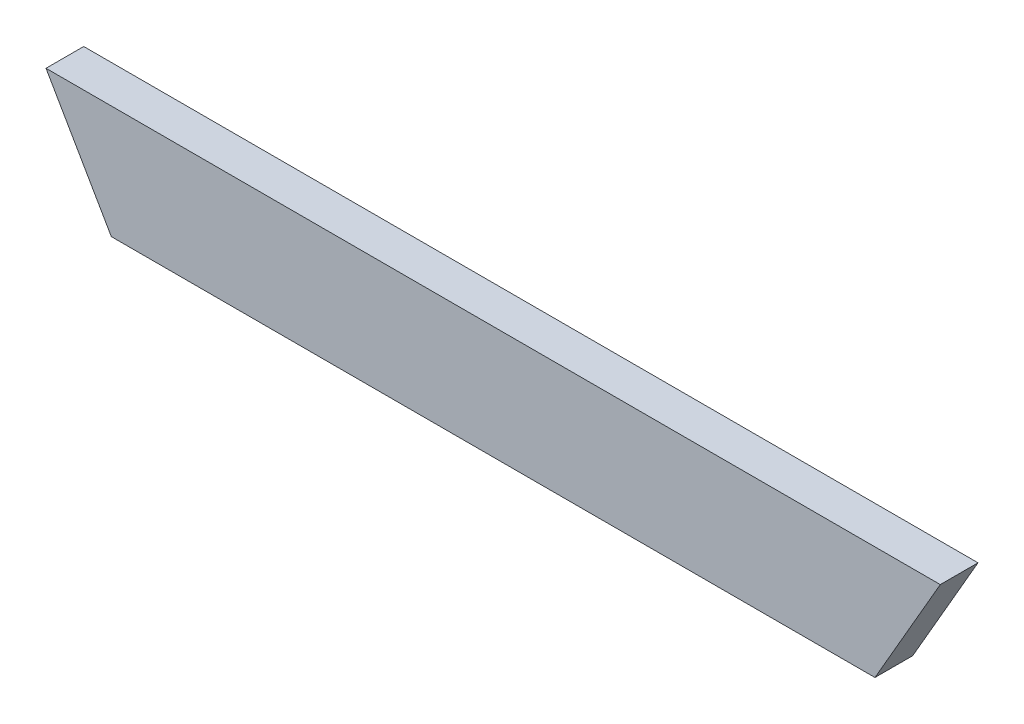
SolidWorks part; units mm, degrees
ref_plane "Plan de face" through (0, 0, 0) normal (0, 0, 1) x (1, 0, 0)
ref_plane "Plan de dessus" through (0, 0, 0) normal (0, 1, 0) x (1, 0, 0)
ref_plane "Plan de droite" through (0, 0, 0) normal (1, 0, 0) x (0, 0, -1)
sketch "Esquisse1" plane through (0, 0, 0) normal (0, 0, 1) x (1, 0, 0)
  line L0 (-225.0031, 84.1096) -> (130.6569, 84.1096)
  line L1 (130.6569, 84.1096) -> (104.6762, 39.1096)
  line L2 (104.6762, 39.1096) -> (-199.0223, 39.1096)
  line L3 (-199.0223, 39.1096) -> (-225.0031, 84.1096)
  dimension "D1" = 355.66
  dimension "D2" = 120
  dimension "D3" = 45
extrude "Boss.-Extru.1" add sketch "Esquisse1" along normal blind 15
